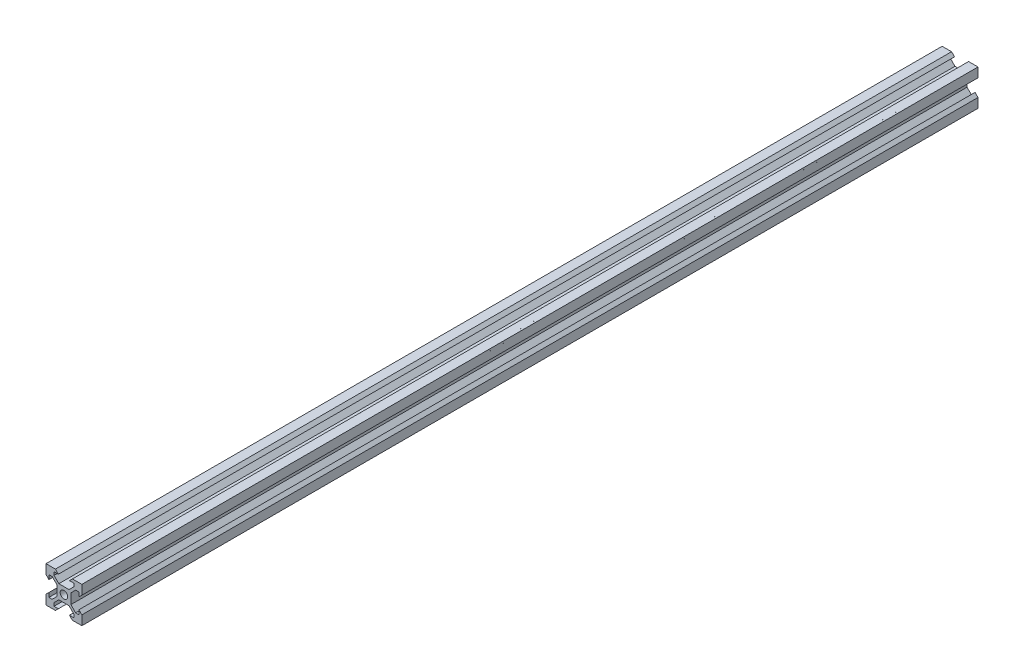
SolidWorks part; units mm, degrees
material "6061-T6 (SS)"
ref_plane "Front Plane" through (0, 0, 0) normal (0, 0, 1) x (1, 0, 0)
ref_plane "Top Plane" through (0, 0, 0) normal (0, 1, 0) x (1, 0, 0)
ref_plane "Right Plane" through (0, 0, 0) normal (1, 0, 0) x (0, 0, -1)
sketch "Sketch1" plane through (0, 0, 0) normal (0, 0, 1) x (1, 0, 0)
  line L0 (2.8343, 3.894) -> (5.5, 6.5588)
  line L1 (2.8343, -3.894) -> (-2.8343, -3.894)
  line L2 (3.8948, -2.8332) -> (3.8948, 2.8332)
  line L3 (2.8343, 3.894) -> (-2.8343, 3.894)
  line L4 (-3.8948, -2.8332) -> (-3.8948, 2.8332)
  line L5 (3.8994, -3.9006) -> (-3.8994, 3.9006) construction
  line L6 (3.9006, 3.8994) -> (-3.9006, -3.8994) construction
  line L7 (10, 4.747) -> (10, 9.9986)
  line L8 (5.5, 6.5588) -> (5.5, 8.3491)
  line L9 (5.5, 8.3491) -> (3.1, 8.3491)
  line L10 (3.1, 8.3491) -> (4.75, 9.9986)
  line L11 (4.75, 9.9986) -> (10, 9.9986)
  line L12 (8.35, 3.0975) -> (10, 4.747)
  line L13 (8.3507, 5.4975) -> (8.35, 3.0975)
  line L14 (6.5605, 5.498) -> (8.3507, 5.4975)
  line L15 (3.8948, 2.8332) -> (6.5605, 5.498)
  line L16 (0, -55) -> (0, 55) construction
  line L17 (-3.8948, 2.8332) -> (-6.5605, 5.498)
  line L18 (-6.5605, 5.498) -> (-8.3507, 5.4975)
  line L19 (-8.3507, 5.4975) -> (-8.35, 3.0975)
  line L20 (-8.35, 3.0975) -> (-10, 4.747)
  line L21 (-4.75, 9.9986) -> (-10, 9.9986)
  line L22 (-3.1, 8.3491) -> (-4.75, 9.9986)
  line L23 (-5.5, 8.3491) -> (-3.1, 8.3491)
  line L24 (-5.5, 6.5588) -> (-5.5, 8.3491)
  line L25 (-10, 4.747) -> (-10, 9.9986)
  line L26 (-2.8343, 3.894) -> (-5.5, 6.5588)
  line L27 (55, 0) -> (-55, 0) construction
  line L28 (3.8948, -2.8332) -> (6.5605, -5.498)
  line L29 (2.8343, -3.894) -> (5.5, -6.5588)
  line L30 (-3.8948, -2.8332) -> (-6.5605, -5.498)
  line L31 (-2.8343, -3.894) -> (-5.5, -6.5588)
  line L32 (-8.3507, -5.4975) -> (-8.35, -3.0975)
  line L33 (-8.35, -3.0975) -> (-10, -4.747)
  line L34 (8.3507, -5.4975) -> (8.35, -3.0975)
  line L35 (8.35, -3.0975) -> (10, -4.747)
  line L36 (-10, -4.747) -> (-10, -9.9986)
  line L37 (-5.5, -6.5588) -> (-5.5, -8.3491)
  line L38 (-5.5, -8.3491) -> (-3.1, -8.3491)
  line L39 (-3.1, -8.3491) -> (-4.75, -9.9986)
  line L40 (-4.75, -9.9986) -> (-10, -9.9986)
  line L41 (-6.5605, -5.498) -> (-8.3507, -5.4975)
  line L42 (6.5605, -5.498) -> (8.3507, -5.4975)
  line L43 (4.75, -9.9986) -> (10, -9.9986)
  line L44 (3.1, -8.3491) -> (4.75, -9.9986)
  line L45 (5.5, -8.3491) -> (3.1, -8.3491)
  line L46 (5.5, -6.5588) -> (5.5, -8.3491)
  line L47 (10, -4.747) -> (10, -9.9986)
  circle A0 centre (0, 0) radius 2.1
  point P0 (0, 0)
  dimension "D6" = 4.2
  dimension "D1" = 7.8
  dimension "D2" = 20
  dimension "D3" = 11
  dimension "D4" = 9.5
  dimension "D5" = 6.2
  dimension "D7" = 1.5
extrude "Boss-Extrude1" add sketch "Sketch1" along normal blind 500
